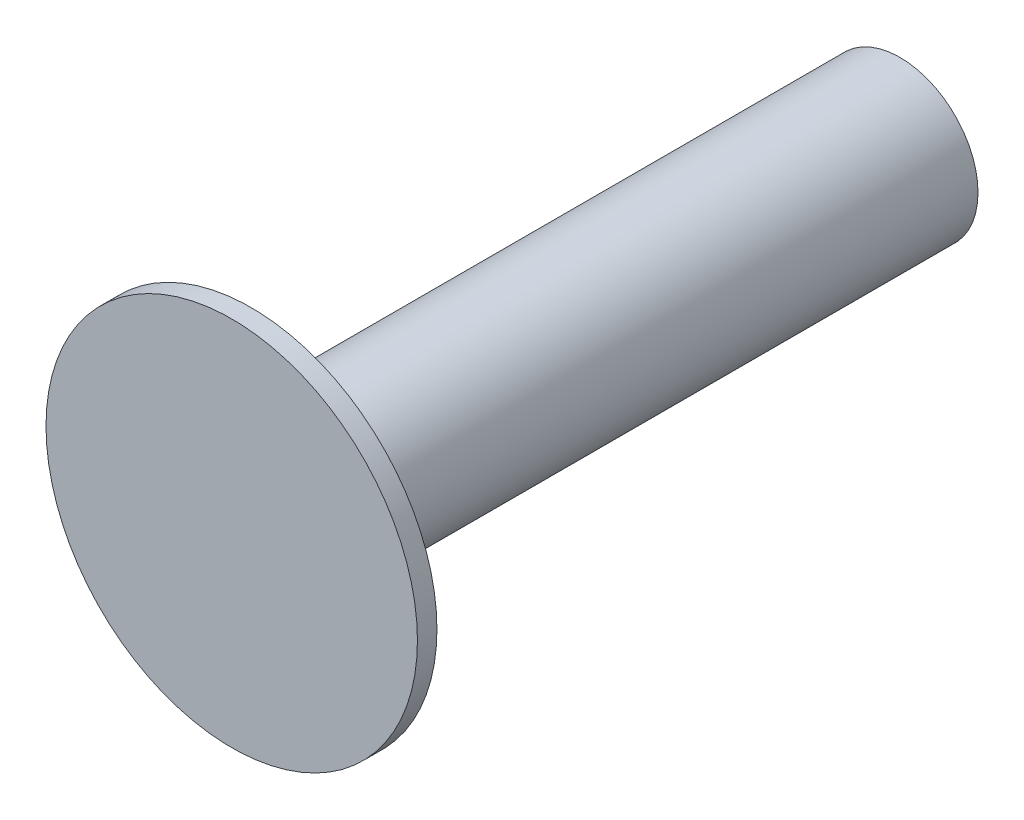
SolidWorks part; units mm, degrees
ref_plane "Front Plane" through (0, 0, 0) normal (0, 0, 1) x (1, 0, 0)
ref_plane "Top Plane" through (0, 0, 0) normal (0, 1, 0) x (1, 0, 0)
ref_plane "Right Plane" through (0, 0, 0) normal (1, 0, 0) x (0, 0, -1)
sketch "Sketch1" plane through (0, 0, 0) normal (0, 0, 1) x (1, 0, 0)
  circle A0 centre (0, 0) radius 4
  dimension "D1" = 8
extrude "Boss-Extrude1" add sketch "Sketch1" along normal blind 33.274
sketch "Sketch2" plane through (0, 0, 33.274) normal (0, 0, 1) x (1, 0, 0)
  circle A0 centre (0, 0) radius 9.525
  dimension "D1" = 19.05
extrude "Boss-Extrude2" add sketch "Sketch2" along normal blind 1
sketch "Sketch3" plane through (0, 0, 0) normal (0, 0, -1) x (-1, 0, 0)
  circle A0 centre (0, 0) radius 2
  dimension "D1" = 4
extrude "Cut-Extrude1" cut sketch "Sketch3" against normal offset from surface (15 mm away) 15 up to face at (4, 0, 0)
